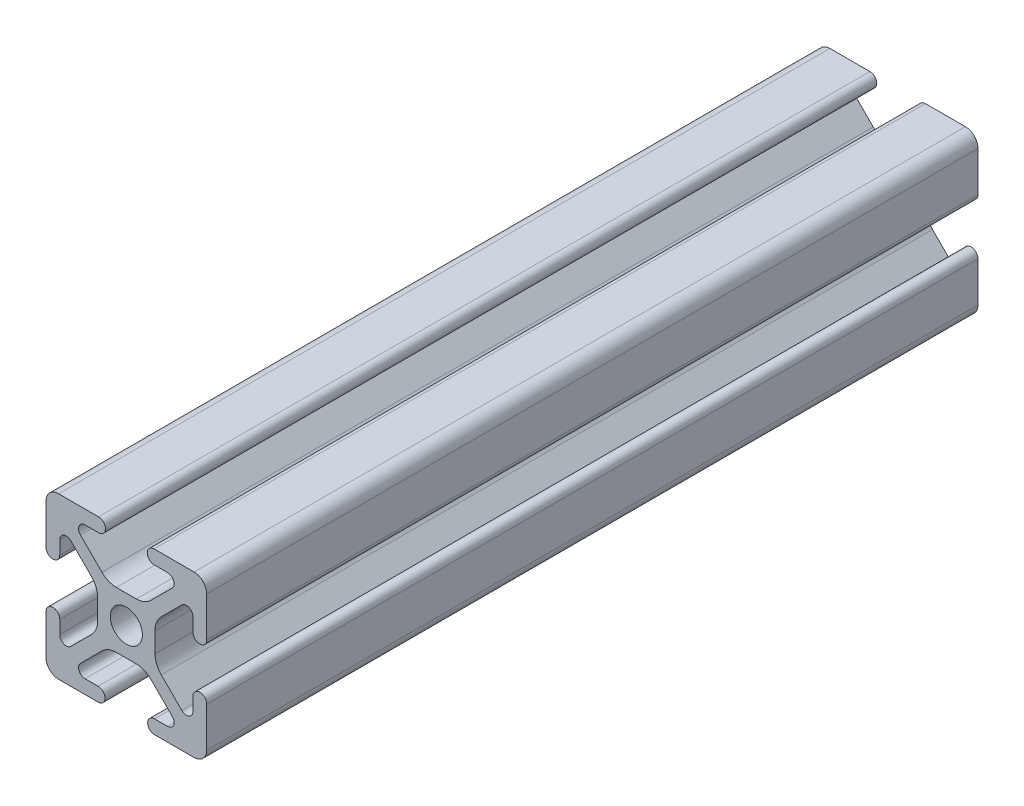
SolidWorks part; units mm, degrees
ref_plane "Front Plane" through (0, 0, 0) normal (0, 0, 1) x (1, 0, 0)
ref_plane "Top Plane" through (0, 0, 0) normal (0, 1, 0) x (1, 0, 0)
ref_plane "Right Plane" through (0, 0, 0) normal (1, 0, 0) x (0, 0, -1)
ref_plane "Plane1" through (0, 0, -25) normal (0, 0, -1) x (-1, 0, 0)
sketch "Sketch1" plane through (0, 0, -25) normal (0, 0, -1) x (-1, 0, 0)
  line L0 (12.5, 4.32) -> (12.5, 10.5371)
  line L1 (10.5371, 12.5) -> (4.32, 12.5)
  line L2 (4.32, 10.36) -> (6.42, 10.36)
  line L3 (7.1337, 8.6353) -> (3.7953, 5.3018)
  line L4 (1.5554, 4.375) -> (-1.5554, 4.375)
  line L5 (-3.7953, 5.3018) -> (-7.1337, 8.6353)
  line L6 (-6.42, 10.36) -> (-4.32, 10.36)
  line L7 (-4.32, 12.5) -> (-10.5371, 12.5)
  line L8 (-12.5, 10.5371) -> (-12.5, 4.32)
  line L9 (-10.36, 4.32) -> (-10.36, 6.3969)
  line L10 (-8.6363, 7.1116) -> (-5.4322, 3.9121)
  line L11 (-4.455, 1.5554) -> (-4.455, -1.5554)
  line L12 (-5.4322, -3.9121) -> (-8.6363, -7.1116)
  line L13 (-10.36, -6.3969) -> (-10.36, -4.32)
  line L14 (-12.5, -4.32) -> (-12.5, -10.5371)
  line L15 (-10.5371, -12.5) -> (-4.3879, -12.5)
  line L16 (-4.3879, -10.36) -> (-6.42, -10.36)
  line L17 (-7.1337, -8.6353) -> (-3.7953, -5.3018)
  line L18 (-1.5554, -4.375) -> (1.5554, -4.375)
  line L19 (3.7953, -5.3018) -> (7.1337, -8.6353)
  line L20 (6.42, -10.36) -> (4.3879, -10.36)
  line L21 (4.3879, -12.5) -> (10.5371, -12.5)
  line L22 (12.5, -10.5371) -> (12.5, -4.32)
  line L23 (10.36, -4.32) -> (10.36, -6.3969)
  line L24 (8.6363, -7.1116) -> (5.4322, -3.9121)
  line L25 (4.455, -1.5554) -> (4.455, 1.5554)
  line L26 (5.4322, 3.9121) -> (8.6363, 7.1116)
  line L27 (10.36, 6.3969) -> (10.36, 4.32)
  circle A0 centre (0, 0) radius 2.5
  arc A1 (12.5, 10.5371) -> (10.5371, 12.5) centre (10.5371, 10.5371) ccw
  arc A2 (4.32, 12.5) -> (4.32, 10.36) centre (4.32, 11.43) ccw
  arc A3 (6.42, 10.36) -> (7.1337, 8.6353) centre (6.42, 9.35) cw
  arc A4 (3.7953, 5.3018) -> (1.5554, 4.375) centre (1.5554, 7.545) cw
  arc A5 (-1.5554, 4.375) -> (-3.7953, 5.3018) centre (-1.5554, 7.545) cw
  arc A6 (-7.1337, 8.6353) -> (-6.42, 10.36) centre (-6.42, 9.35) cw
  arc A7 (-4.32, 10.36) -> (-4.32, 12.5) centre (-4.32, 11.43) ccw
  arc A8 (-10.5371, 12.5) -> (-12.5, 10.5371) centre (-10.5371, 10.5371) ccw
  arc A9 (-12.5, 4.32) -> (-10.36, 4.32) centre (-11.43, 4.32) ccw
  arc A10 (-10.36, 6.3969) -> (-8.6363, 7.1116) centre (-9.35, 6.3969) cw
  arc A11 (-5.4322, 3.9121) -> (-4.455, 1.5554) centre (-7.7855, 1.5554) cw
  arc A12 (-4.455, -1.5554) -> (-5.4322, -3.9121) centre (-7.7855, -1.5554) cw
  arc A13 (-8.6363, -7.1116) -> (-10.36, -6.3969) centre (-9.35, -6.3969) cw
  arc A14 (-10.36, -4.32) -> (-12.5, -4.32) centre (-11.43, -4.32) ccw
  arc A15 (-12.5, -10.5371) -> (-10.5371, -12.5) centre (-10.5371, -10.5371) ccw
  arc A16 (-4.3879, -12.5) -> (-4.3879, -10.36) centre (-4.3879, -11.43) ccw
  arc A17 (-6.42, -10.36) -> (-7.1337, -8.6353) centre (-6.42, -9.35) cw
  arc A18 (-3.7953, -5.3018) -> (-1.5554, -4.375) centre (-1.5554, -7.545) cw
  arc A19 (1.5554, -4.375) -> (3.7953, -5.3018) centre (1.5554, -7.545) cw
  arc A20 (7.1337, -8.6353) -> (6.42, -10.36) centre (6.42, -9.35) cw
  arc A21 (4.3879, -10.36) -> (4.3879, -12.5) centre (4.3879, -11.43) ccw
  arc A22 (10.5371, -12.5) -> (12.5, -10.5371) centre (10.5371, -10.5371) ccw
  arc A23 (12.5, -4.32) -> (10.36, -4.32) centre (11.43, -4.32) ccw
  arc A24 (10.36, -6.3969) -> (8.6363, -7.1116) centre (9.35, -6.3969) cw
  arc A25 (5.4322, -3.9121) -> (4.455, -1.5554) centre (7.7855, -1.5554) cw
  arc A26 (4.455, 1.5554) -> (5.4322, 3.9121) centre (7.7855, 1.5554) cw
  arc A27 (8.6363, 7.1116) -> (10.36, 6.3969) centre (9.35, 6.3969) cw
  arc A28 (10.36, 4.32) -> (12.5, 4.32) centre (11.43, 4.32) ccw
extrude "Boss-Extrude1" add sketch "Sketch1" against normal blind 120
